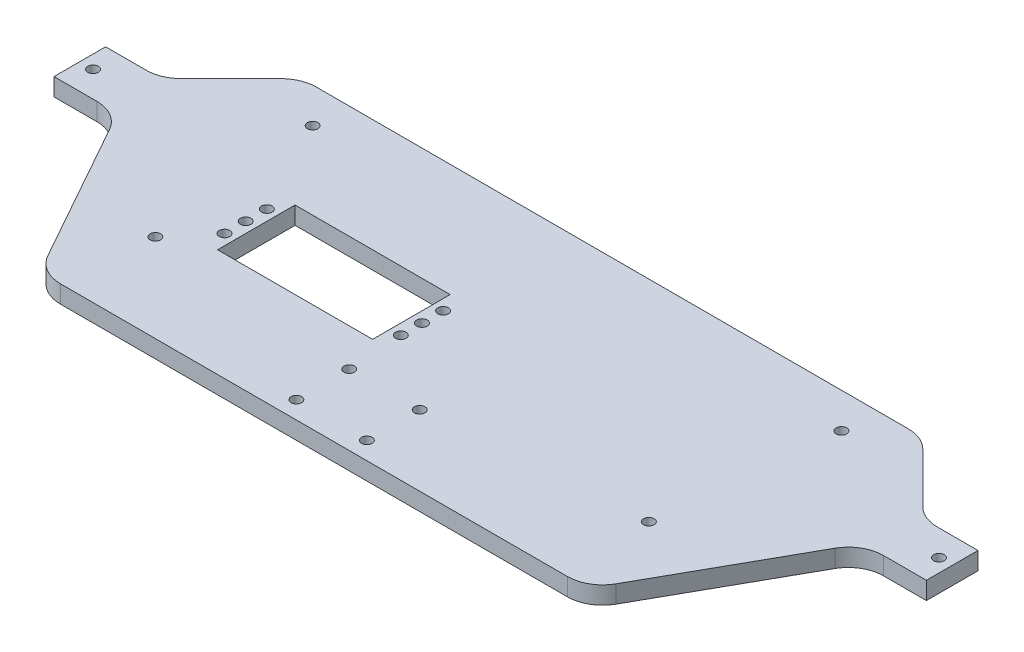
SolidWorks part; units mm, degrees
ref_plane "Alzado" through (0, 0, 0) normal (0, 0, 1) x (1, 0, 0)
ref_plane "Planta" through (0, 0, 0) normal (0, 1, 0) x (1, 0, 0)
ref_plane "Vista lateral" through (0, 0, 0) normal (1, 0, 0) x (0, 0, -1)
sketch "Croquis1" plane through (0, 0, 0) normal (0, 1, 0) x (1, 0, 0)
  line L0 (-27.8825, 0) -> (38.5584, 0) construction
  line L1 (-88.1, 42.3182) -> (88.1, 42.3182)
  line L2 (-77.75, -42.3182) -> (77.75, -42.3182)
  line L3 (-88.1, 42.3182) -> (-108.1, 22.3182)
  line L4 (-108.1, 22.3182) -> (-127.75, 22.3182)
  line L5 (0, 0) -> (0, 27.7067) construction
  line L6 (-127.75, 22.3182) -> (-127.75, 7.6818)
  line L7 (-127.75, 7.6818) -> (-105.75, 7.6818)
  line L8 (-105.75, 7.6818) -> (-77.75, -42.3182)
  line L9 (88.1, 42.3182) -> (108.1, 22.3182)
  line L10 (108.1, 22.3182) -> (127.75, 22.3182)
  line L11 (127.75, 22.3182) -> (127.75, 7.6818)
  line L12 (127.75, 7.6818) -> (105.75, 7.6818)
  line L13 (105.75, 7.6818) -> (77.75, -42.3182)
  dimension "D1" = 255.5
  dimension "D2" = 84.6363
  dimension "D3" = 19.65
  dimension "D4" = 22
  dimension "D5" = 22
  dimension "D6" = 50
  dimension "D7" = 50
  dimension "D8" = 50
  dimension "D9" = 20
  dimension "D10" = 20
  dimension "D11" = 19.65
extrude "Saliente-Extruir1" add sketch "Croquis1" along normal blind 5
fillet "Redondeo1" radius 10 8 edges at (88.1, 2.5, -42.3182) (-88.1, 2.5, -42.3182) (-77.75, 2.5, 42.3182) (77.75, 2.5, 42.3182) (108.1, 2.5, -22.3182) (105.75, 2.5, -7.6818) (-105.75, 2.5, -7.6818) (-108.1, 2.5, -22.3182)
sketch "Croquis2" plane through (0, 5, 0) normal (0, 1, 0) x (1, 0, 0)
  line L0 (0, 0) -> (0, -87.7887) construction
  line L1 (-119.9961, 22.3182) -> (-119.9961, 40.4374) construction
  line L2 (-112.2421, 22.3182) -> (-127.75, 22.3182) construction
  line L3 (-127.75, 15) -> (-123.2915, 15) construction
  line L4 (-127.75, 22.3182) -> (-127.75, 7.6818) construction
  line L5 (119.9961, 22.3182) -> (119.9961, 29.1715) construction
  line L6 (127.75, 22.3182) -> (112.2421, 22.3182) construction
  line L7 (115.6048, 15) -> (126.3231, 15) construction
  line L8 (83.9579, 42.3182) -> (-83.9579, 42.3182) construction
  line L9 (-57, 9.3182) -> (-15, 9.3182)
  line L10 (-71.8888, -42.3182) -> (71.8888, -42.3182) construction
  line L11 (-15, 9.3182) -> (-15, -10.6818)
  line L12 (-15, -10.6818) -> (-57, -10.6818)
  line L13 (-57, -10.6818) -> (-57, 9.3182)
  line L14 (-57, -0.6818) -> (-2.6959, -0.6818) construction
  line L15 (-36, 9.3182) -> (-36, 33.9331) construction
  line L16 (-11, -0.6818) -> (-11, 14.1752) construction
  line L17 (-61, -0.6818) -> (-61, -3.5648) construction
  circle A0 centre (70, -17.3182) radius 1.5
  circle A1 centre (-70, -17.3182) radius 1.5
  circle A2 centre (-119.9961, 15) radius 1.5
  circle A3 centre (119.9961, 15) radius 1.5
  circle A4 centre (-75, 32.3182) radius 1.5
  circle A5 centre (75, 32.3182) radius 1.5
  circle A6 centre (-10, -22.3182) radius 1.5
  circle A7 centre (10, -22.3182) radius 1.5
  circle A8 centre (-10, -37.3182) radius 1.5
  circle A9 centre (10, -37.3182) radius 1.5
  circle A10 centre (-61, -0.6818) radius 1.5
  circle A11 centre (-11, -0.6818) radius 1.5
  circle A12 centre (-61, 5.3182) radius 1.5
  circle A13 centre (-61, -6.6818) radius 1.5
  circle A14 centre (-11, 5.3182) radius 1.5
  circle A15 centre (-11, -6.6818) radius 1.5
  dimension "D1" = 3
  dimension "D2" = 3
  dimension "D7" = 3
  dimension "D8" = 3
  dimension "D10" = 3
  dimension "D11" = 3
  dimension "D17" = 3
  dimension "D18" = 3
  dimension "D19" = 3
  dimension "D20" = 3
  dimension "D25" = 50
  dimension "D27" = 3
  dimension "D28" = 3
  dimension "D29" = 3
  dimension "D30" = 3
  dimension "D31" = 3
  dimension "D32" = 3
  dimension "D3" = 75
  dimension "D4" = 75
  dimension "D5" = 10
  dimension "D6" = 10
  dimension "D9" = 140
  dimension "D12" = 25
  dimension "D13" = 20
  dimension "D14" = 20
  dimension "D15" = 5
  dimension "D16" = 15
  dimension "D21" = 42
  dimension "D22" = 20
  dimension "D23" = 30
  dimension "D24" = 33
  dimension "D26" = 50
  dimension "D33" = 6
  dimension "D34" = 6
  dimension "D35" = 6
  dimension "D36" = 6
extrude "Cortar-Extruir1" cut sketch "Croquis2" against normal through all
sketch "Croquis3" plane through (0, 5, 0) normal (0, 1, 0) x (1, 0, 0)
  line L0 (-123.75, 22.3182) -> (-123.75, 7.6818)
  line L1 (-112.2421, 22.3182) -> (-127.75, 22.3182) construction
  line L2 (-127.75, 7.6818) -> (-111.6112, 7.6818) construction
  line L3 (-123.75, 7.6818) -> (-127.75, 7.6818)
  line L4 (-127.75, 7.6818) -> (-127.75, 22.3182)
  line L5 (-127.75, 22.3182) -> (-123.75, 22.3182)
  line L6 (127.75, 7.6818) -> (127.75, 22.3182)
  line L7 (127.75, 22.3182) -> (123.75, 22.3182)
  line L8 (127.75, 22.3182) -> (112.2421, 22.3182) construction
  line L9 (123.75, 22.3182) -> (123.75, 7.6818)
  line L10 (111.6112, 7.6818) -> (127.75, 7.6818) construction
  line L11 (123.75, 7.6818) -> (127.75, 7.6818)
  dimension "D1" = 4
  dimension "D2" = 4
extrude "Cortar-Extruir2" cut sketch "Croquis3" against normal through all
sketch "Croquis4" plane through (0, 5, 0) normal (0, 1, 0) x (1, 0, 0)
  line L0 (-36, 9.3182) -> (-36, -16.9775) construction
  line L1 (-15, 9.3182) -> (-57, 9.3182) construction
  line L2 (-57, -0.6818) -> (-47.1795, -0.6818) construction
  line L3 (-57, 9.3182) -> (-57, -10.6818) construction
  line L4 (-58, 10.3182) -> (-58, -11.6818)
  line L5 (-58, -11.6818) -> (-14, -11.6818)
  line L6 (-14, -11.6818) -> (-14, 10.3182)
  line L7 (-58, 10.3182) -> (-14, 10.3182)
  line L8 (-15, -10.6818) -> (-15, 9.3182) construction
  line L9 (-57, -10.6818) -> (-15, -10.6818) construction
  dimension "D1" = 1
  dimension "D2" = 1
  dimension "D3" = 1
  dimension "D4" = 1
extrude "Cortar-Extruir3" cut sketch "Croquis4" against normal through all
